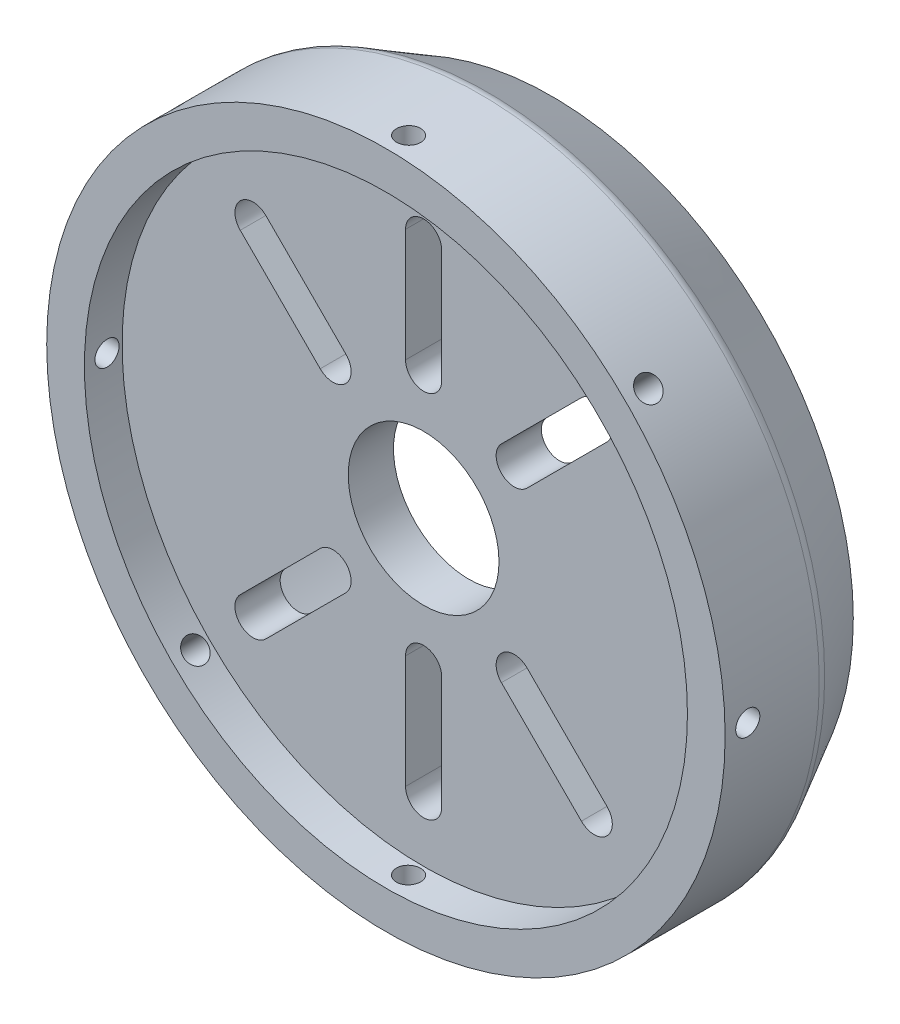
SolidWorks part; units mm, degrees
material "Nickel silver 65-12, UNS C75700"
ref_plane "Front Plane" through (0, 0, 0) normal (0, 0, 1) x (1, 0, 0)
ref_plane "Top Plane" through (0, 0, 0) normal (0, 1, 0) x (1, 0, 0)
ref_plane "Right Plane" through (0, 0, 0) normal (1, 0, 0) x (0, 0, -1)
sketch "Sketch1" plane through (0, 0, 0) normal (1, 0, 0) x (0, 0, -1)
  line L0 (0, 0) -> (33.2772, 0) construction
  line L1 (0, 12.7) -> (0, 50.8)
  line L2 (0, 50.8) -> (-6.35, 50.8)
  line L3 (-6.35, 50.8) -> (-6.35, 57.15)
  line L4 (-6.35, 57.15) -> (10.16, 57.15)
  line L5 (10.16, 57.15) -> (21.59, 50.8)
  line L6 (21.59, 50.8) -> (21.59, 45.72)
  line L7 (21.59, 45.72) -> (7.62, 45.72)
  line L8 (7.62, 45.72) -> (7.62, 12.7)
  line L9 (7.62, 12.7) -> (0, 12.7)
  point P12 (0, 0)
  point P13 (0, 0)
  dimension "D1" = 6.35
  dimension "D2" = 16.51
  dimension "D3" = 6.35
  dimension "D4" = 5.08
  dimension "D5" = 13.97
  dimension "D6" = 12.7
  dimension "D7" = 7.62
  dimension "D8" = 50.8
  dimension "D9" = 11.43
revolve "Revolve1" add sketch "Sketch1" angle 360 about L0
sketch "Sketch2" plane through (0, 0, 0) normal (0, 0, 1) x (1, 0, 0)
  line L0 (0, 21.59) -> (0, 40.64) construction
  line L1 (-3.048, 21.59) -> (-3.048, 40.64)
  line L2 (3.048, 21.59) -> (3.048, 40.64)
  arc A0 (-3.048, 21.59) -> (3.048, 21.59) centre (0, 21.59) ccw
  arc A1 (3.048, 40.64) -> (-3.048, 40.64) centre (0, 40.64) ccw
  point P3 (0, 31.115)
  dimension "D2" = 3.048
  dimension "D1" = 19.05
  dimension "D3" = 21.59
extrude "Cut-Extrude1" cut sketch "Sketch2" against normal through all
pattern_circular "CirPattern1" count 8 over 360 about axis through (0, 0, 0) along (0, 0, 1) skipping 2, 6 of "Cut-Extrude1"
sketch "Sketch3" plane through (0, 0, 0) normal (0, 1, 0) x (1, 0, 0)
  line L0 (-57.15, -6.35) -> (57.15, -6.35) construction
  circle A0 centre (0, -2.54) radius 2.032
  point P4 (0, 0)
  point P7 (0, 0)
  dimension "D1" = 4.064
  dimension "D2" = 3.81
extrude "Cut-Extrude2" cut sketch "Sketch3" against normal through all
pattern_circular "CirPattern2" count 8 over 360 about axis through (0, 0, 0) along (0, 0, 1) of "Cut-Extrude2"
fillet "Fillet1" radius 2.54 1 edges at (57.15, 0, -10.16)
